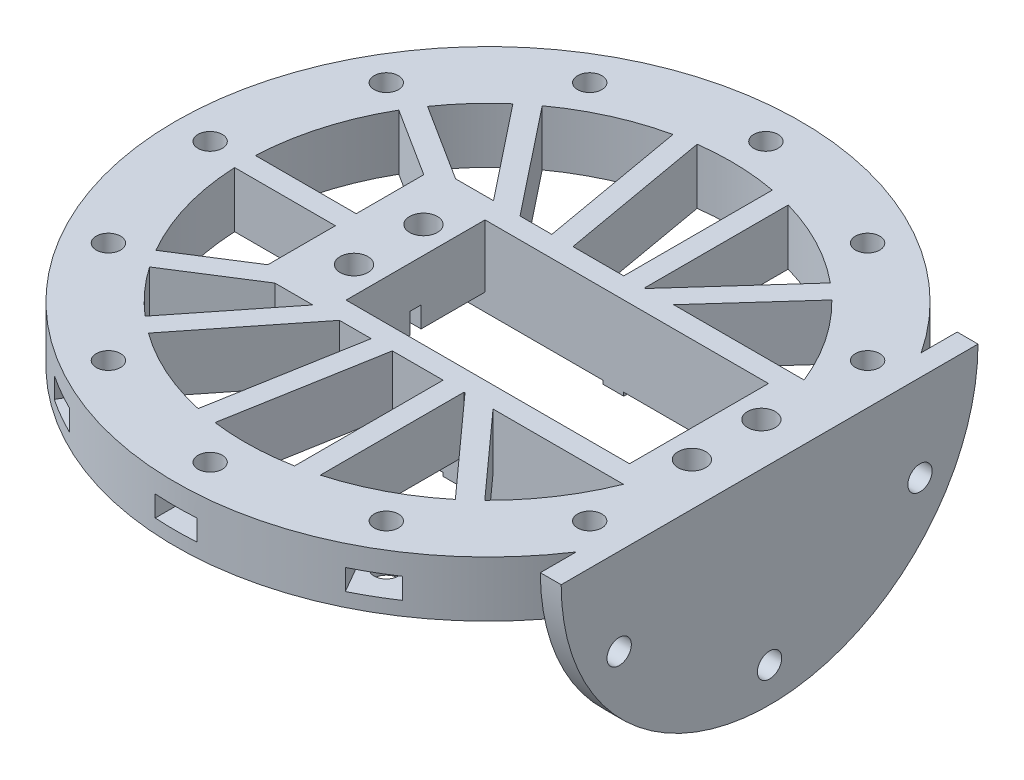
SolidWorks part; units mm, degrees
ref_plane "Front Plane" through (0, 0, 0) normal (0, 0, 1) x (1, 0, 0)
ref_plane "Top Plane" through (0, 0, 0) normal (0, 1, 0) x (1, 0, 0)
ref_plane "Right Plane" through (0, 0, 0) normal (1, 0, 0) x (0, 0, -1)
sketch "Sketch1" plane through (0, 0, 0) normal (0, 1, 0) x (1, 0, 0)
  line L0 (-43.0464, 0) -> (41.9462, 0) construction
  line L1 (0, 43.1152) -> (0, -41.8775) construction
  circle A1 centre (0, 0) radius 45
  dimension "D2" = 90
extrude "Boss-Extrude1" add sketch "Sketch1" along normal blind 12
sketch "Sketch2" plane through (0, 0, 0) normal (0, -1, 0) x (1, 0, 0)
  circle A0 centre (0, 0) radius 35
  dimension "D1" = 70
extrude "Cut-Extrude1" cut sketch "Sketch2" against normal blind 0.5
sketch "Sketch3" plane through (0, 0.5, 0) normal (0, -1, 0) x (1, 0, 0)
  line L0 (35, 0) -> (-35, 0) construction
  line L1 (0, -35) -> (0, 35) construction
  line L3 (37.5324, -10) -> (-17.4676, -10)
  line L4 (37.5324, -10) -> (37.5324, 10)
  line L5 (37.5324, 10) -> (-17.4676, 10)
  line L6 (-17.4676, -10) -> (-17.4676, 10)
  circle A0 centre (0, 0) radius 35 construction
  circle A1 centre (0, 0) radius 35 construction
  dimension "D1" = 20
  dimension "D2" = 55
  dimension "D3" = 10
  dimension "D4" = 37.5324
extrude "Cut-Extrude2" cut sketch "Sketch3" against normal blind 2.5 and the other way up to next
sketch "Sketch4" plane through (0, 3, 0) normal (0, -1, 0) x (1, 0, 0)
  line L0 (37.5324, 0) -> (-17.4676, 0) construction
  line L1 (37.5324, 10) -> (37.5324, -10) construction
  line L2 (-17.4676, 10) -> (-17.4676, -10) construction
  line L3 (0, -10) -> (0, 10) construction
  line L4 (-17.4676, -10) -> (33.541, -10) construction
  line L5 (33.541, 10) -> (-17.4676, 10) construction
  line L7 (30.3722, -10) -> (-10.4278, -10)
  line L8 (30.3722, -10) -> (30.3722, 10)
  line L9 (30.3722, 10) -> (-10.4278, 10)
  line L10 (-10.4278, -10) -> (-10.4278, 10)
  dimension "D1" = 20
  dimension "D2" = 40.8
  dimension "D3" = 30.3722
  dimension "D4" = 10
extrude "Cut-Extrude3" cut sketch "Sketch4" against normal blind 9
sketch "Sketch8" plane through (0, 0.5, 0) normal (0, -1, 0) x (1, 0, 0)
  line L0 (-17.4676, 0) -> (-35, 0) construction
  line L1 (-17.4676, 10) -> (-17.4676, -10) construction
  line L2 (8.0367, 10) -> (8.0367, 34.0648) construction
  line L3 (33.541, 10) -> (-17.4676, 10) construction
  line L4 (8.0367, -10) -> (8.0367, -29.3194) construction
  line L5 (-17.4676, -10) -> (33.541, -10) construction
  line L6 (6.5367, 10) -> (6.5367, 34.3842)
  line L7 (9.5367, 10) -> (9.5367, 33.6757)
  line L8 (9.5367, 10) -> (6.5367, 10)
  line L9 (9.5367, -10) -> (6.5367, -10)
  line L10 (6.5367, -10) -> (6.5367, -34.3842)
  line L11 (9.5367, -10) -> (9.5367, -33.6757)
  line L12 (-17.4676, 1.5) -> (-34.9678, 1.5)
  line L13 (-17.4676, -1.5) -> (-34.9678, -1.5)
  line L14 (-17.4676, 1.5) -> (-17.4676, -1.5)
  arc A0 (33.541, 10) -> (33.541, -10) centre (0, 0) ccw construction
  arc A1 (9.5367, 33.6757) -> (6.5367, 34.3842) centre (7.9531, 33.6757) ccw
  arc A2 (9.5367, -33.6757) -> (6.5367, -34.3842) centre (7.9531, -33.6757) cw
  arc A3 (-34.9678, 1.5) -> (-34.9678, -1.5) centre (-34.9678, 0) ccw
  dimension "D3" = 1.5
  dimension "D1" = 1.5
  dimension "D2" = 1.5
  dimension "D4" = 1.5
extrude "Boss-Extrude2" add sketch "Sketch8" along normal through all
sketch "Sketch16" plane through (0, 3, 0) normal (0, -1, 0) x (1, 0, 0)
  line L0 (-17.4676, 0) -> (37.5324, 0) construction
  line L1 (-17.4676, 10) -> (-17.4676, -10) construction
  line L2 (37.5324, -10) -> (37.5324, 10) construction
  line L3 (30.3722, -0.8) -> (37.5324, -0.8)
  line L4 (-10.4278, -0.8) -> (-17.4676, -0.8)
  line L5 (-10.4278, 10) -> (-10.4278, -10) construction
  line L6 (-10.4278, 0.8) -> (-17.4676, 0.8)
  line L7 (-17.4676, 0.8) -> (-17.4676, -0.8)
  line L8 (-10.4278, 0.8) -> (-10.4278, -0.8)
  line L9 (30.3722, -10) -> (30.3722, 10) construction
  line L10 (30.3722, 0.8) -> (37.5324, 0.8)
  line L11 (37.5324, 0.8) -> (37.5324, -0.8)
  line L12 (30.3722, 0.8) -> (30.3722, -0.8)
  dimension "D1" = 0.8
extrude "Cut-Extrude10" cut sketch "Sketch16" against normal blind 3
sketch "Sketch27" plane through (0, 0, 0) normal (0, -1, 0) x (1, 0, 0)
  line L0 (0, 0) -> (0, -53.17) construction
  line L1 (0, 0) -> (47.7582, -27.5732) construction
  line L3 (31.641, -18.2679) -> (31.641, -21.7321) construction
  line L4 (31.641, -21.7321) -> (34.641, -23.4641) construction
  line L5 (34.641, -23.4641) -> (37.641, -21.7321) construction
  line L6 (37.641, -21.7321) -> (37.641, -18.2679) construction
  line L7 (37.641, -18.2679) -> (34.641, -16.5359) construction
  line L8 (34.641, -16.5359) -> (31.641, -18.2679) construction
  circle A0 centre (0, 0) radius 40 construction
  circle A1 centre (34.641, -20) radius 1.75
  circle A2 centre (0, 0) radius 35 construction
  circle A3 centre (34.641, -20) radius 3 construction
  circle A4 centre (20, -34.641) radius 1.75
  circle A5 centre (0, -40) radius 1.75
  circle A6 centre (-20, -34.641) radius 1.75
  circle A7 centre (-34.641, -20) radius 1.75
  circle A8 centre (-40, 0) radius 1.75
  circle A9 centre (-34.641, 20) radius 1.75
  circle A10 centre (-20, 34.641) radius 1.75
  circle A11 centre (0, 40) radius 1.75
  circle A12 centre (20, 34.641) radius 1.75
  circle A13 centre (34.641, 20) radius 1.75
  circle A15 centre (40, 0) radius 1.75 [skipped]
  point P28 (0, 0)
  point P41 (0, 0)
  dimension "D1" = 80
  dimension "D3" = 3.5
  dimension "D4" = 70
  dimension "D5" = 6
  dimension "D6" = 12
  dimension "D2" = 60
extrude "Cut-Extrude15" cut sketch "Sketch27" against normal through all
ref_plane "Plane1" through (0, 9, 0) normal (0, 1, 0) x (1, 0, 0)
sketch "Sketch28" plane through (0, 9, 0) normal (0, 1, 0) x (1, 0, 0)
  line L0 (0, 0) -> (-54.493, 0) construction
  line L1 (-31.641, 18.2679) -> (-31.641, 21.7321)
  line L2 (-36.5359, 0) -> (-38.2679, 3)
  line L3 (-38.2679, 3) -> (-44.8999, 3)
  line L4 (-31.641, 21.7321) -> (-37.3844, 25.048)
  line L5 (-40.3844, 19.8519) -> (-34.641, 16.5359)
  line L6 (-44.8999, -3) -> (-38.2679, -3)
  line L7 (-38.2679, -3) -> (-36.5359, 0)
  line L8 (-43.4641, 0) -> (-42.5981, -1.5) [skipped]
  line L9 (-41.7321, 3) -> (-42.5981, 1.5) [skipped]
  line L10 (-34.641, 16.5359) -> (-31.641, 18.2679)
  line L11 (-18.2679, 31.641) -> (-16.5359, 34.641)
  line L12 (-16.5359, 34.641) -> (-19.8519, 40.3844)
  line L13 (-25.048, 37.3844) -> (-21.7321, 31.641)
  line L14 (-21.7321, 31.641) -> (-18.2679, 31.641)
  line L15 (0, 36.5359) -> (3, 38.2679)
  line L16 (3, 38.2679) -> (3, 44.8999)
  line L17 (-3, 44.8999) -> (-3, 38.2679)
  line L18 (-3, 38.2679) -> (0, 36.5359)
  line L19 (18.2679, 31.641) -> (21.7321, 31.641)
  line L20 (21.7321, 31.641) -> (25.048, 37.3844)
  line L21 (19.8519, 40.3844) -> (16.5359, 34.641)
  line L22 (16.5359, 34.641) -> (18.2679, 31.641)
  line L23 (31.641, 18.2679) -> (34.641, 16.5359)
  line L24 (34.641, 16.5359) -> (40.3844, 19.8519)
  line L25 (37.3844, 25.048) -> (31.641, 21.7321)
  line L26 (31.641, 21.7321) -> (31.641, 18.2679)
  line L31 (31.641, -18.2679) -> (31.641, -21.7321)
  line L32 (31.641, -21.7321) -> (37.3844, -25.048)
  line L33 (40.3844, -19.8519) -> (34.641, -16.5359)
  line L34 (34.641, -16.5359) -> (31.641, -18.2679)
  line L35 (18.2679, -31.641) -> (16.5359, -34.641)
  line L36 (16.5359, -34.641) -> (19.8519, -40.3844)
  line L37 (25.048, -37.3844) -> (21.7321, -31.641)
  line L38 (21.7321, -31.641) -> (18.2679, -31.641)
  line L39 (0, -36.5359) -> (-3, -38.2679)
  line L40 (-3, -38.2679) -> (-3, -44.8999)
  line L41 (3, -44.8999) -> (3, -38.2679)
  line L42 (3, -38.2679) -> (0, -36.5359)
  line L43 (-18.2679, -31.641) -> (-21.7321, -31.641)
  line L44 (-21.7321, -31.641) -> (-25.048, -37.3844)
  line L45 (-19.8519, -40.3844) -> (-16.5359, -34.641)
  line L46 (-16.5359, -34.641) -> (-18.2679, -31.641)
  line L47 (-31.641, -18.2679) -> (-34.641, -16.5359)
  line L48 (-34.641, -16.5359) -> (-40.3844, -19.8519)
  line L49 (-37.3844, -25.048) -> (-31.641, -21.7321)
  line L50 (-31.641, -21.7321) -> (-31.641, -18.2679)
  line L51 (36.5359, 0) -> (38.2679, -3) [skipped]
  line L52 (38.2679, -3) -> (44.8999, -3) [skipped]
  line L53 (44.8999, 3) -> (38.2679, 3) [skipped]
  line L54 (38.2679, 3) -> (36.5359, 0) [skipped]
  arc A0 (-44.8999, 3) -> (-44.8999, -3) centre (0, 0) ccw
  circle A1 centre (-40, 0) radius 3 construction
  arc A2 (-37.3844, 25.048) -> (-40.3844, 19.8519) centre (0, 0) ccw
  circle A3 centre (-34.641, 20) radius 3 construction
  arc A4 (-19.8519, 40.3844) -> (-25.048, 37.3844) centre (0, 0) ccw
  circle A5 centre (-20, 34.641) radius 3 construction
  arc A6 (3, 44.8999) -> (-3, 44.8999) centre (0, 0) ccw
  circle A7 centre (0, 40) radius 3 construction
  arc A8 (25.048, 37.3844) -> (19.8519, 40.3844) centre (0, 0) ccw
  circle A9 centre (20, 34.641) radius 3 construction
  arc A10 (40.3844, 19.8519) -> (37.3844, 25.048) centre (0, 0) ccw
  circle A11 centre (34.641, 20) radius 3 construction
  arc A14 (37.3844, -25.048) -> (40.3844, -19.8519) centre (0, 0) ccw
  circle A15 centre (34.641, -20) radius 3 construction
  arc A16 (19.8519, -40.3844) -> (25.048, -37.3844) centre (0, 0) ccw
  circle A17 centre (20, -34.641) radius 3 construction
  arc A18 (-3, -44.8999) -> (3, -44.8999) centre (0, 0) ccw
  circle A19 centre (0, -40) radius 3 construction
  arc A20 (-25.048, -37.3844) -> (-19.8519, -40.3844) centre (0, 0) ccw
  circle A21 centre (-20, -34.641) radius 3 construction
  arc A22 (-40.3844, -19.8519) -> (-37.3844, -25.048) centre (0, 0) ccw
  circle A23 centre (-34.641, -20) radius 3 construction
  arc A24 (44.8999, -3) -> (44.8999, 3) centre (0, 0) ccw [skipped]
  circle A25 centre (40, 0) radius 3 construction
  point P94 (0, 0)
  dimension "D1" = 90
  dimension "D2" = 6
  dimension "D3" = 12
extrude "Cut-Extrude17" cut sketch "Sketch28" against normal blind 3
sketch "Sketch29" plane through (0, 0.5, 0) normal (0, -1, 0) x (1, 0, 0)
  line L0 (32.4962, -13) -> (13.7255, -13)
  line L1 (9.5367, -33.6757) -> (9.5367, -10) construction
  line L2 (9.5367, -13) -> (9.5367, -33.6757)
  line L3 (9.5367, -10) -> (33.541, -10) construction
  line L4 (6.5367, -13) -> (-0.7691, -13)
  line L5 (6.5367, -10) -> (6.5367, -34.3842) construction
  line L6 (-20.4676, -11.223) -> (-20.4676, -1.5)
  line L7 (-34.9678, -1.5) -> (-17.4676, -1.5) construction
  line L8 (-20.4676, -1.5) -> (-34.9678, -1.5)
  line L9 (-17.4676, -0.8) -> (-17.4676, -10) construction
  line L10 (32.4962, 13) -> (13.7255, 13)
  line L11 (9.5367, 10) -> (9.5367, 33.6757) construction
  line L12 (9.5367, 13) -> (9.5367, 33.6757)
  line L13 (-7.5493, 34.1761) -> (-3.8154, 13)
  line L14 (6.5367, 13) -> (-0.7691, 13)
  line L15 (6.5367, 34.3842) -> (6.5367, 10) construction
  line L16 (-20.4676, 11.223) -> (-20.4676, 1.5)
  line L17 (-17.4676, 1.5) -> (-34.9678, 1.5) construction
  line L18 (-20.4676, 1.5) -> (-34.9678, 1.5)
  line L19 (6.5367, 13) -> (6.5367, 34.3842)
  line L20 (6.5367, -34.3842) -> (6.5367, -13)
  line L21 (0, 0) -> (-21.7353, -27.4331) construction
  line L22 (-20.5397, -28.3394) -> (-8.3862, -13)
  line L23 (-22.8911, -26.4764) -> (-12.2137, -13)
  line L24 (0, 0) -> (-20.4676, -13) construction
  line L25 (-17.6698, -13) -> (-28.713, -20.0141)
  line L26 (-20.4676, -11.223) -> (-30.3215, -17.4817)
  line L27 (0, 0) -> (-35, 0) construction
  line L28 (-20.4676, 11.223) -> (-30.3215, 17.4817)
  line L29 (-17.6698, 13) -> (-28.713, 20.0141)
  line L30 (-22.8911, 26.4764) -> (-12.2137, 13)
  line L31 (-20.5397, 28.3394) -> (-8.3862, 13)
  line L32 (-12.2137, 13) -> (-17.6698, 13)
  line L33 (0, 0) -> (-6.0777, -34.4683) construction
  line L34 (-4.5949, -34.6971) -> (-0.7691, -13)
  line L35 (-7.5493, -34.1761) -> (-3.8154, -13)
  line L36 (-3.8154, -13) -> (-17.6698, -13)
  line L37 (-4.5949, 34.6971) -> (-0.7691, 13)
  line L38 (-3.8154, 13) -> (-8.3862, 13)
  line L39 (0, 0) -> (23.4214, -26.0084) construction
  line L40 (9.6883, -13) -> (22.2852, -26.9883)
  line L41 (13.7255, -13) -> (24.5145, -24.9808)
  line L42 (13.7255, 13) -> (24.5145, 24.9808)
  line L43 (9.6883, 13) -> (22.2852, 26.9883)
  line L44 (9.6883, -13) -> (9.5367, -13)
  line L45 (9.6883, 13) -> (9.5367, 13)
  arc A0 (9.5367, -33.6757) -> (22.2852, -26.9883) centre (0, 0) ccw
  arc A1 (6.5367, 34.3842) -> (-4.5949, 34.6971) centre (0, 0) ccw
  arc A2 (32.4962, 13) -> (24.5145, 24.9808) centre (0, 0) ccw
  arc A3 (-34.9678, -1.5) -> (-30.3215, -17.4817) centre (0, 0) ccw
  circle A4 centre (0, 0) radius 35 construction
  arc A5 (-7.5493, 34.1761) -> (-20.5397, 28.3394) centre (0, 0) ccw
  arc A6 (-4.5949, -34.6971) -> (6.5367, -34.3842) centre (0, 0) ccw
  arc A7 (-20.5397, -28.3394) -> (-7.5493, -34.1761) centre (0, 0) ccw
  arc A8 (-28.713, -20.0141) -> (-22.8911, -26.4764) centre (0, 0) ccw
  arc A9 (-30.3215, 17.4817) -> (-34.9678, 1.5) centre (0, 0) ccw
  arc A10 (-22.8911, 26.4764) -> (-28.713, 20.0141) centre (0, 0) ccw
  arc A11 (24.5145, -24.9808) -> (32.4962, -13) centre (0, 0) ccw
  arc A12 (22.2852, 26.9883) -> (9.5367, 33.6757) centre (0, 0) ccw
  point P11 (21.5389, -10)
  point P23 (-17.4676, -5.4)
  line M3 (-17.4676, -1.5) -> (-34.9678, -1.5)
  arc M4 (-34.9678, -1.5) -> (6.5367, -34.3842) centre (0, 0) ccw
  line M5 (6.5367, -34.3842) -> (6.5367, -10)
  dimension "D1" = 1.5
  dimension "D2" = 3
  dimension "D3" = 3
  dimension "D4" = 80
  dimension "D5" = 1.5
  dimension "D6" = 1.5
  dimension "D7" = 1.5
sketch "Sketch32" plane through (0, 3, 0) normal (0, -1, 0) x (1, 0, 0)
  line L0 (-17.4676, 0) -> (37.5324, 0) construction
  line L1 (-17.4676, -1.5) -> (-17.4676, 1.5) construction
  line L2 (37.5324, 10) -> (37.5324, -10) construction
  line L3 (10.0324, 0) -> (10.0324, -10) construction
  line L6 (9.5367, -10) -> (33.541, -10) construction
  circle A0 centre (-14.2876, -5) radius 2
  circle A1 centre (-14.2876, 5) radius 2
  circle A2 centre (34.3524, -5) radius 2
  circle A3 centre (34.3524, 5) radius 2
  dimension "D1" = 24.32
  dimension "D3" = 4
  dimension "D2" = 5
extrude "Cut-Extrude21" cut sketch "Sketch32" against normal through all
extrude "Cut-Extrude22" cut sketch "Sketch29" against normal blind 12 contours L28 A9 L18 L16 | L26 L6 M3 M4 | L23 L36 L25 M4 | L35 L36 L22 M4 | L34 L4 M4 M5 | L2 A0 L40 L44 | L41 A11 L0 | L10 A2 L42 | L43 A12 L12 L45 | L19 A1 L37 L14 | L13 A5 L31 L38 | L30 A10 L29 L32
sketch "Sketch33" plane through (0, 0, 0) normal (0, -1, 0) x (1, 0, 0)
  line L0 (37.5324, 0) -> (37.5324, 38.7806) construction
  line L1 (37.5324, 10) -> (37.5324, -10) construction
  line L3 (37.5324, 38.7806) -> (47.0341, 38.7806)
  line L4 (37.5324, 38.7806) -> (37.5324, -37.2389)
  line L5 (37.5324, -37.2389) -> (47.0341, -37.2389)
  line L6 (47.0341, 38.7806) -> (47.0341, -37.2389)
extrude "Cut-Extrude24" cut sketch "Sketch33" against normal through all
sketch "Sketch34" plane through (37.5324, 0, 0) normal (1, 0, 0) x (0, 0, -1)
  line L0 (-24.8258, 12) -> (24.8258, 12) construction
  line L1 (30, 12) -> (-30, 12)
  arc A0 (-30, 12) -> (30, 12) centre (0, 12) ccw
  dimension "D1" = 30
  dimension "D2" = 60
extrude "Boss-Extrude3" add sketch "Sketch34" along normal blind 3
sketch "Sketch35" plane through (37.5324, 0, 0) normal (-1, 0, 0) x (0, 0, 1)
  line L0 (24.8258, 0) -> (10, 0) construction
  line L1 (13, 0) -> (50, 0)
  line L2 (13, 0) -> (13, 4)
  line L3 (13, 4) -> (50, 4)
  line L4 (50, 0) -> (50, 4)
  line L5 (40.3844, 6) -> (37.3844, 6) construction
  line L6 (0, 6) -> (0, 9) construction
  line L7 (-13, 0) -> (-13, 4)
  line L8 (-13, 4) -> (-50, 4)
  line L9 (-13, 0) -> (-50, 0)
  line L10 (-50, 0) -> (-50, 4)
  dimension "D1" = 2
  dimension "D2" = 13
  dimension "D3" = 50
extrude "Cut-Extrude26" cut sketch "Sketch35" along normal blind 90
sketch "Sketch36" plane through (0, 0, 0) normal (0, 0, 1) x (1, 0, 0)
  line L0 (-17.4676, 0) -> (-17.4676, 0.5)
  line L1 (-17.4676, 0.5) -> (-20.4676, 0.5)
  line L2 (-20.4676, 0.5) -> (-23.2653, 4)
  line L3 (-23.2653, 4) -> (-47.4962, 4)
  line L4 (-47.4962, 4) -> (-47.4962, 0)
  line L5 (-47.4962, 0) -> (-17.4676, 0)
  line L6 (-32.4962, 0) -> (-32.4962, 4) construction
  dimension "D1" = 15
extrude "Cut-Extrude27" cut sketch "Sketch36" against normal through all both and the other way through all
sketch "Sketch37" plane through (40.5324, 0, 0) normal (1, 0, 0) x (0, 0, -1)
  line L0 (0, 12) -> (0, -18) construction
  line L1 (30, 12) -> (-30, 12) construction
  arc A0 (-30, 12) -> (30, 12) centre (0, 12) ccw construction
  circle A1 centre (0, -13) radius 1.75
  circle A2 centre (-21.6506, -0.5) radius 1.75
  circle A6 centre (21.6506, -0.5) radius 1.75
  circle A7 centre (-21.6506, 24.5) radius 1.75 [skipped]
  circle A8 centre (0, 37) radius 1.75 [skipped]
  circle A9 centre (21.6506, 24.5) radius 1.75 [skipped]
  point P21 (0, 12)
  dimension "D2" = 3.5
  dimension "D1" = 25
  dimension "D3" = 6
extrude "Cut-Extrude28" cut sketch "Sketch37" against normal up to next
